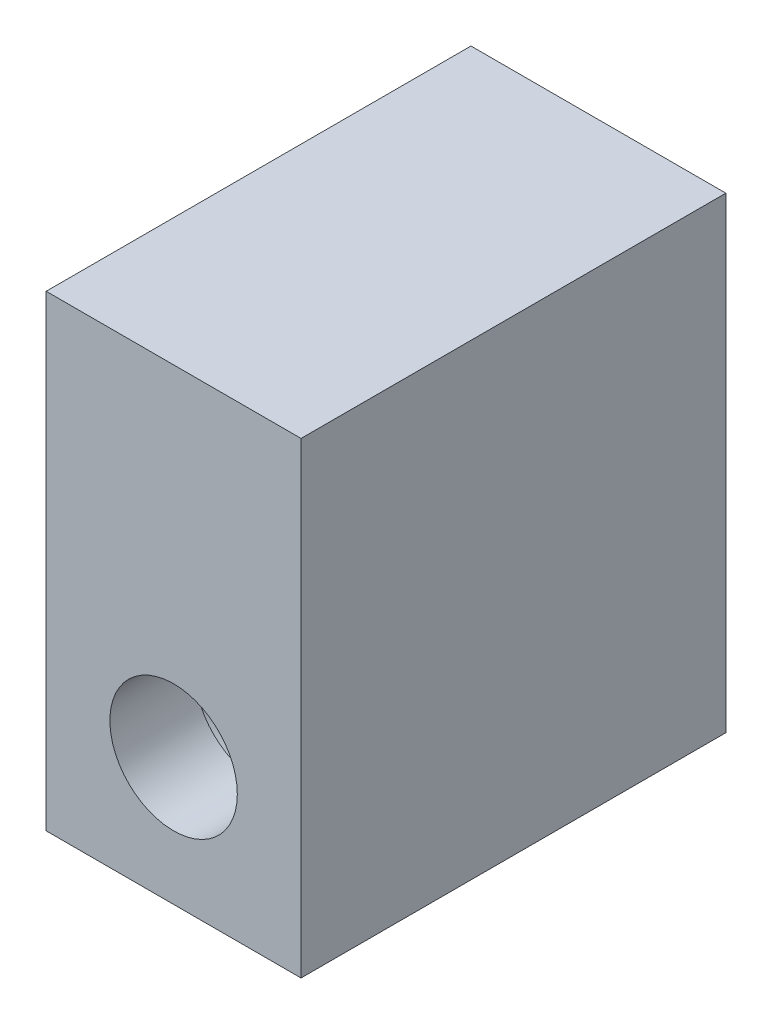
SolidWorks part; units mm, degrees
material "PVC Rigid"
ref_plane "Front Plane" through (0, 0, 0) normal (0, 0, 1) x (1, 0, 0)
ref_plane "Top Plane" through (0, 0, 0) normal (0, 1, 0) x (1, 0, 0)
ref_plane "Right Plane" through (0, 0, 0) normal (1, 0, 0) x (0, 0, -1)
sketch "Sketch1" plane through (0, 0, 0) normal (0, 0, 1) x (1, 0, 0)
  line L1 (0, 0) -> (-50, 0)
  line L2 (0, 0) -> (0, 70)
  line L3 (0, 70) -> (-50, 70)
  line L4 (-50, 0) -> (-50, 70)
  dimension "D1" = 50
  dimension "D2" = 70
extrude "Boss-Extrude1" add sketch "Sketch1" along normal blind 10
sketch "Sketch2" plane through (0, 0, 10) normal (0, 0, 1) x (1, 0, 0)
  line L0 (-50, 0) -> (0, 0) construction
  line L1 (-50, 70) -> (-50, 0) construction
  circle A0 centre (-25, 15) radius 7.5
  dimension "D1" = 15
  dimension "D2" = 25
extrude "Cut-Extrude1" cut sketch "Sketch2" against normal blind 10
sketch "Sketch3" plane through (0, 0, 0) normal (0, 0, -1) x (-1, 0, 0)
  line L1 (0, 70) -> (50, 70)
  line L2 (0, 70) -> (0, 0)
  line L3 (0, 0) -> (50, 0)
  line L4 (50, 70) -> (50, 0)
extrude "Boss-Extrude2" add sketch "Sketch3" along normal blind 40
sketch "Sketch4" plane through (0, 0, -40) normal (0, 0, -1) x (-1, 0, 0)
  line L0 (0, 70) -> (0, 0) construction
  line L2 (0, 0) -> (50, 0) construction
  circle A0 centre (25, 15) radius 10.5
  point P4 (0, 0)
  point P6 (25.9355, 0)
  dimension "D1" = 25
  dimension "D2" = 15
extrude "Cut-Extrude3" cut sketch "Sketch4" against normal blind 40
sketch "Sketch5" plane through (0, 0, -40) normal (0, 0, -1) x (-1, 0, 0)
  line L0 (0, 0) -> (50, 0) construction
  line L1 (0, 70) -> (10, 70)
  line L2 (0, 70) -> (0, 0)
  line L3 (0, 0) -> (10, 0)
  line L4 (10, 70) -> (10, 0)
  line L6 (50, 70) -> (40, 70)
  line L7 (50, 70) -> (50, 0)
  line L8 (50, 0) -> (40, 0)
  line L9 (40, 70) -> (40, 0)
  dimension "D1" = 10
  dimension "D2" = 10
extrude "Cut-Extrude4" cut sketch "Sketch5" against normal blind 50
sketch "Sketch6" plane through (-40, 0, 0) normal (-1, 0, 0) x (0, 0, 1)
  line L0 (10, 0) -> (-40, 0) construction
  line L2 (-40, 70) -> (-40, 0) construction
  line L3 (10, 70) -> (10, 0) construction
  circle A0 centre (-27.5, 40) radius 6
  circle A1 centre (-2.5, 40) radius 6
  dimension "D3" = 12.5
  dimension "D1" = 40
  dimension "D2" = 40
  dimension "D4" = 12.5
extrude "Cut-Extrude5" cut sketch "Sketch6" against normal blind 20
sketch "Sketch7" plane through (-40, 0, 0) normal (-1, 0, 0) x (0, 0, 1)
  line L0 (10, 70) -> (10, 0) construction
  line L1 (-40, 70) -> (10, 70)
  line L2 (-40, 70) -> (-40, 55)
  line L3 (-40, 55) -> (10, 55)
  line L4 (10, 70) -> (10, 55)
  dimension "D1" = 15
extrude "Cut-Extrude6" cut sketch "Sketch7" against normal blind 30
